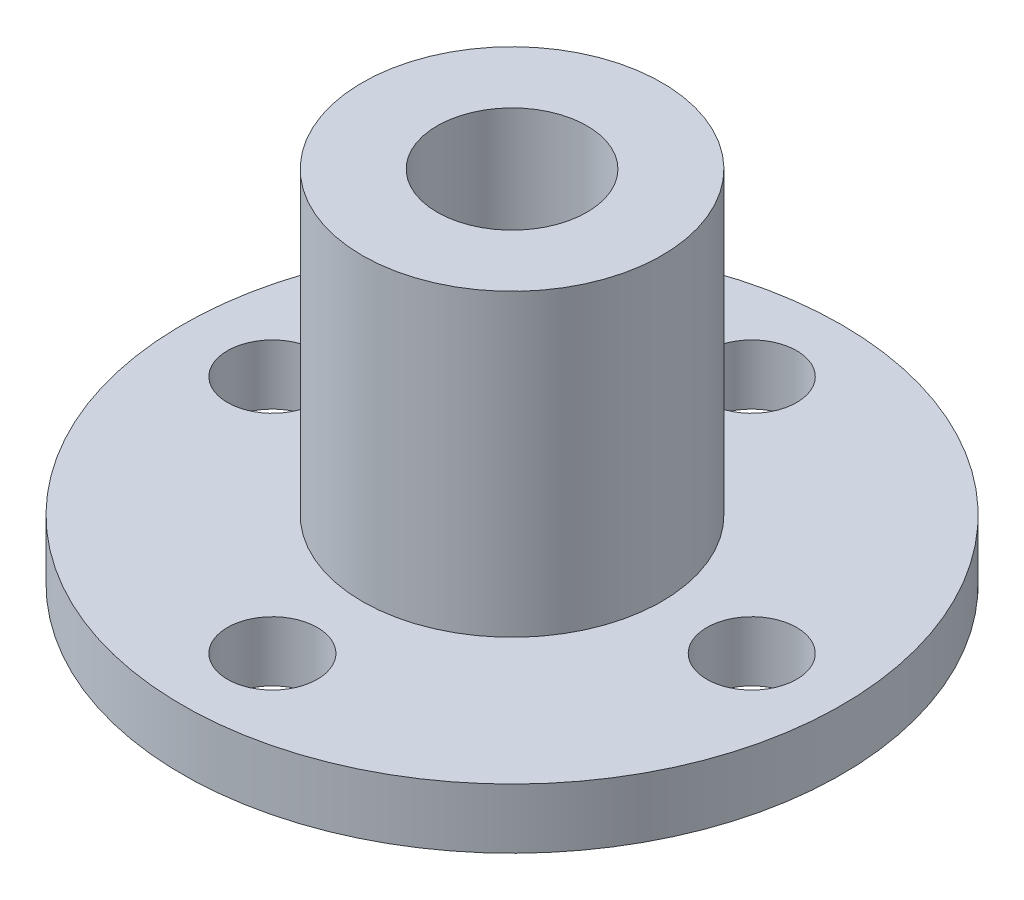
SolidWorks part; units mm, degrees
material "AISI 304"
ref_plane "前视基准面" through (0, 0, 0) normal (0, 0, 1) x (1, 0, 0)
ref_plane "上视基准面" through (0, 0, 0) normal (0, 1, 0) x (1, 0, 0)
ref_plane "右视基准面" through (0, 0, 0) normal (1, 0, 0) x (0, 0, -1)
other "Configuration Table"
sketch "草图1" plane through (0, 0, 0) normal (0, 1, 0) x (1, 0, 0)
  circle A0 centre (0, 0) radius 5
  circle A1 centre (0, 0) radius 2.5
  dimension "D1" = 10
  dimension "D2" = 5
extrude "凸台-拉伸1" add sketch "草图1" along normal blind 10
sketch "草图2" plane through (0, 0, 0) normal (0, -1, 0) x (1, 0, 0)
  line L0 (0, 0) -> (0, 16.6207) construction
  line L1 (0, 0) -> (24.7855, 0) construction
  circle A0 centre (0, 0) radius 11
  circle A1 centre (0, 8) radius 1.5
  circle A2 centre (8, 0) radius 1.5
  circle A3 centre (-8, 0) radius 1.5
  circle A4 centre (0, -8) radius 1.5
  circle A5 centre (0, 0) radius 1.5
  dimension "D1" = 22
  dimension "D2" = 3
  dimension "D3" = 3
  dimension "D4" = 16
  dimension "D5" = 16
  dimension "D6" = 3
extrude "凸台-拉伸2" add sketch "草图2" along normal blind 2
